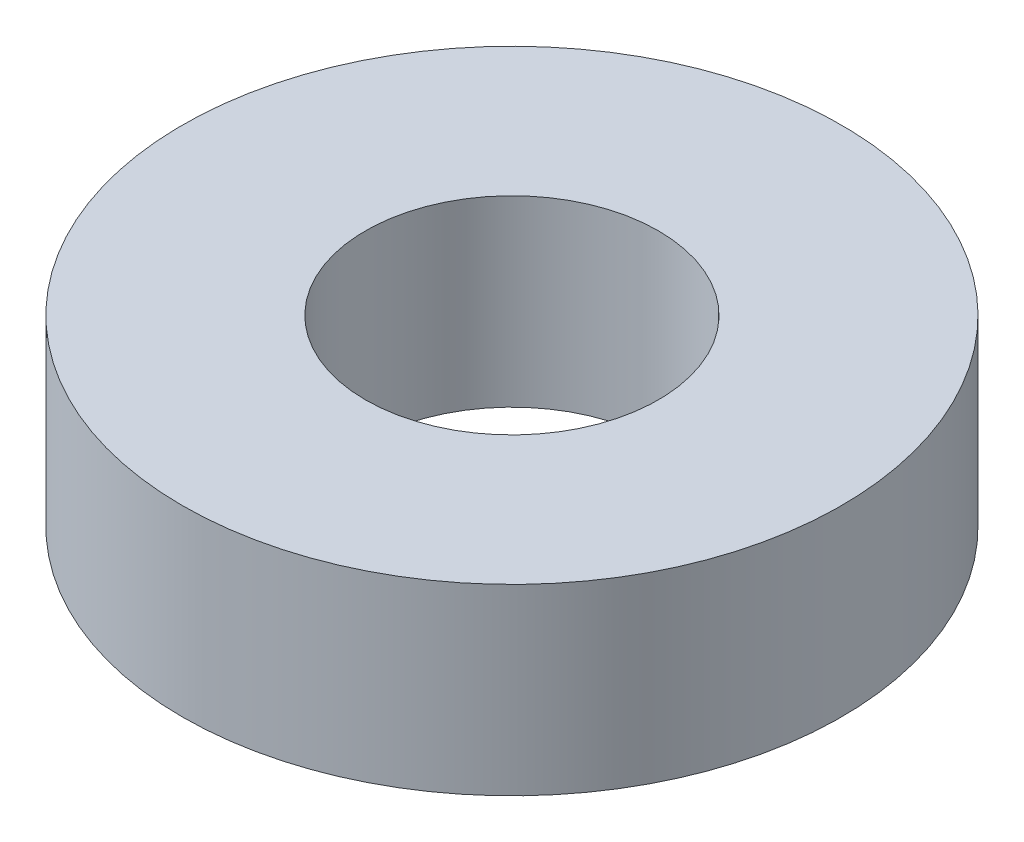
SolidWorks part; units mm, degrees
ref_plane "Front Plane" through (0, 0, 0) normal (0, 0, 1) x (1, 0, 0)
ref_plane "Top Plane" through (0, 0, 0) normal (0, 1, 0) x (1, 0, 0)
ref_plane "Right Plane" through (0, 0, 0) normal (1, 0, 0) x (0, 0, -1)
sketch "Sketch1" plane through (0, 0, 0) normal (0, 1, 0) x (1, 0, 0)
  circle A0 centre (0, 0) radius 14.2875
  circle A1 centre (0, 0) radius 6.35
extrude "Boss-Extrude1" add sketch "Sketch1" along normal blind 7.9375
